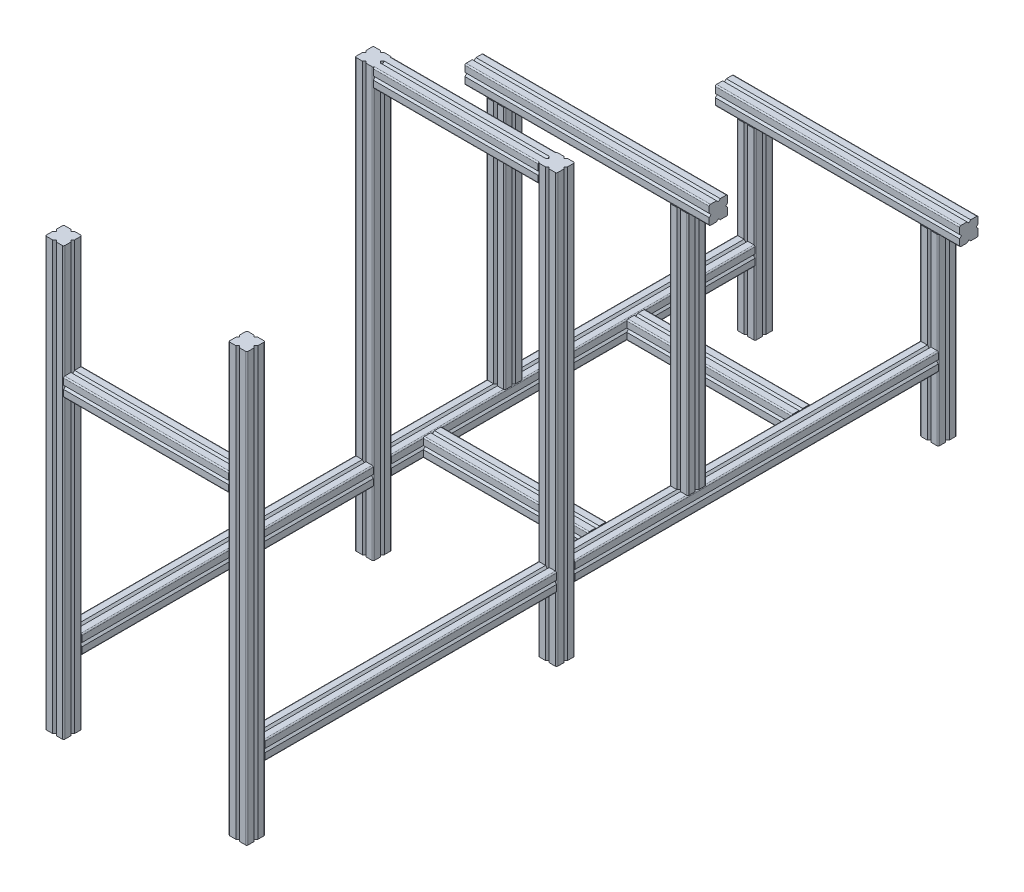
SolidWorks part; units mm, degrees
ref_plane "정면" through (0, 0, 0) normal (0, 0, 1) x (1, 0, 0)
ref_plane "윗면" through (0, 0, 0) normal (0, 1, 0) x (1, 0, 0)
ref_plane "우측면" through (0, 0, 0) normal (1, 0, 0) x (0, 0, -1)
sketch "스케치1" plane through (0, 0, 0) normal (0, 1, 0) x (1, 0, 0)
  line L0 (-150, 0) -> (150, 0) construction
  line L1 (135, 15) -> (165, 15) construction
  line L2 (135, 15) -> (135, -15) construction
  line L3 (135, -15) -> (165, -15) construction
  line L4 (165, 15) -> (165, -15) construction
  line L5 (135, 15) -> (165, -15) construction
  line L6 (135, -15) -> (165, 15) construction
  line L7 (-163, 15) -> (-153, 15)
  line L8 (-165, 13) -> (-165, 3)
  line L9 (-163, -15) -> (-153, -15)
  line L10 (-135, 13) -> (-135, 3)
  line L11 (-165, 15) -> (-135, -15) construction
  line L12 (-165, -15) -> (-135, 15) construction
  line L13 (-153, 15) -> (-150, 12)
  line L14 (-150, 12) -> (-147, 15)
  line L15 (-153, -15) -> (-150, -12)
  line L16 (-150, -12) -> (-147, -15)
  line L17 (-165, -3) -> (-162, 0)
  line L18 (-162, 0) -> (-165, 3)
  line L19 (-135, -3) -> (-138, 0)
  line L20 (-138, 0) -> (-135, 3)
  line L21 (-147, 15) -> (-137, 15)
  line L22 (-165, -3) -> (-165, -13)
  line L23 (-135, -3) -> (-135, -13)
  line L24 (-147, -15) -> (-137, -15)
  line L25 (0, 0) -> (0, 15) construction
  line L26 (165, -15) -> (135, 15) construction
  line L27 (165, 15) -> (135, -15) construction
  line L28 (147, -15) -> (137, -15)
  line L29 (135, -3) -> (135, -13)
  line L30 (165, -3) -> (165, -13)
  line L31 (147, 15) -> (137, 15)
  line L32 (138, 0) -> (135, 3)
  line L33 (135, -3) -> (138, 0)
  line L34 (162, 0) -> (165, 3)
  line L35 (165, -3) -> (162, 0)
  line L36 (150, -12) -> (147, -15)
  line L37 (153, -15) -> (150, -12)
  line L38 (150, 12) -> (147, 15)
  line L39 (153, 15) -> (150, 12)
  line L40 (135, 13) -> (135, 3)
  line L41 (163, -15) -> (153, -15)
  line L42 (165, 13) -> (165, 3)
  line L43 (163, 15) -> (153, 15)
  arc A0 (163, 15) -> (165, 13) centre (163, 13) cw
  arc A1 (163, -15) -> (165, -13) centre (163, -13) ccw
  arc A2 (135, -13) -> (137, -15) centre (137, -13) ccw
  arc A3 (135, 13) -> (137, 15) centre (137, 13) cw
  arc A4 (-137, -15) -> (-135, -13) centre (-137, -13) ccw
  arc A5 (-165, -13) -> (-163, -15) centre (-163, -13) ccw
  arc A6 (-163, 15) -> (-165, 13) centre (-163, 13) ccw
  arc A7 (-137, 15) -> (-135, 13) centre (-137, 13) cw
  point P0 (150, 0)
  point P5 (-150, 0)
  point P12 (0, 0)
  dimension "D2" = 2
  dimension "D1" = 300
  dimension "D4" = 30
  dimension "D6" = 6
extrude "보스-돌출1" add sketch "스케치1" along normal blind 700
sketch "스케치2" plane through (0, 0, 0) normal (0, 1, 0) x (1, 0, 0)
  line L0 (0, 0) -> (0, 625) construction
  line L1 (0, 625) -> (150, 625) construction
  line L2 (147, 640) -> (150, 637)
  line L3 (137, 610) -> (147, 610)
  line L4 (135, 612) -> (135, 622)
  line L5 (137, 640) -> (147, 640)
  line L6 (165, 612) -> (165, 622)
  line L7 (135, 610) -> (165, 640) construction
  line L8 (135, 640) -> (165, 610) construction
  line L9 (150, 637) -> (153, 640)
  line L10 (162, 625) -> (165, 628)
  line L11 (165, 622) -> (162, 625)
  line L12 (153, 610) -> (150, 613)
  line L13 (150, 613) -> (147, 610)
  line L14 (138, 625) -> (135, 622)
  line L15 (135, 628) -> (138, 625)
  line L16 (153, 640) -> (163, 640)
  line L17 (165, 628) -> (165, 638)
  line L18 (153, 610) -> (163, 610)
  line L19 (135, 628) -> (135, 638)
  line L20 (-135, 640) -> (-165, 610) construction
  line L21 (-135, 610) -> (-165, 640) construction
  line L22 (-135, 628) -> (-135, 638)
  line L23 (-153, 610) -> (-163, 610)
  line L24 (-165, 628) -> (-165, 638)
  line L25 (-153, 640) -> (-163, 640)
  line L26 (-135, 628) -> (-138, 625)
  line L27 (-138, 625) -> (-135, 622)
  line L28 (-150, 613) -> (-147, 610)
  line L29 (-153, 610) -> (-150, 613)
  line L30 (-165, 622) -> (-162, 625)
  line L31 (-162, 625) -> (-165, 628)
  line L32 (-150, 637) -> (-153, 640)
  line L33 (-165, 612) -> (-165, 622)
  line L50 (-137, 640) -> (-147, 640)
  line L51 (-135, 612) -> (-135, 622)
  line L52 (-137, 610) -> (-147, 610)
  line L53 (-147, 640) -> (-150, 637)
  arc A0 (-165, 612) -> (-163, 610) centre (-163, 612) ccw
  arc A1 (-137, 610) -> (-135, 612) centre (-137, 612) ccw
  arc A2 (-137, 640) -> (-135, 638) centre (-137, 638) cw
  arc A3 (-163, 640) -> (-165, 638) centre (-163, 638) ccw
  arc A4 (163, 610) -> (165, 612) centre (163, 612) ccw
  arc A5 (137, 610) -> (135, 612) centre (137, 612) cw
  arc A6 (163, 640) -> (165, 638) centre (163, 638) cw
  arc A7 (135, 638) -> (137, 640) centre (137, 638) cw
  point P15 (163.5, 623.5)
  point P16 (151.5, 611.5)
  point P39 (-151.5, 611.5)
  dimension "D4" = 2
  dimension "D1" = 625
  dimension "D2" = 150
  dimension "D3" = 30
  dimension "D5" = 6
extrude "보스-돌출2" add sketch "스케치2" along normal blind 300 separate body
sketch "스케치3" plane through (0, 0, 0) normal (0, 1, 0) x (1, 0, 0)
  line L0 (0, 0) -> (0, -507) construction
  line L1 (0, -507) -> (150, -507) construction
  line L2 (147, -492) -> (150, -495)
  line L3 (137, -522) -> (147, -522)
  line L4 (135, -520) -> (135, -510)
  line L5 (137, -492) -> (147, -492)
  line L6 (165, -520) -> (165, -510)
  line L7 (135, -522) -> (165, -492) construction
  line L8 (135, -492) -> (165, -522) construction
  line L9 (150, -495) -> (153, -492)
  line L10 (165, -510) -> (162, -507)
  line L11 (162, -507) -> (165, -504)
  line L12 (153, -522) -> (150, -519)
  line L13 (150, -519) -> (147, -522)
  line L14 (135, -504) -> (138, -507)
  line L15 (138, -507) -> (135, -510)
  line L16 (153, -492) -> (163, -492)
  line L17 (165, -504) -> (165, -494)
  line L18 (153, -522) -> (163, -522)
  line L19 (135, -504) -> (135, -494)
  line L20 (-135, -492) -> (-165, -522) construction
  line L21 (-135, -522) -> (-165, -492) construction
  line L22 (-135, -504) -> (-135, -494)
  line L23 (-153, -522) -> (-163, -522)
  line L24 (-165, -504) -> (-165, -494)
  line L25 (-153, -492) -> (-163, -492)
  line L26 (-138, -507) -> (-135, -510)
  line L27 (-135, -504) -> (-138, -507)
  line L28 (-150, -519) -> (-147, -522)
  line L29 (-153, -522) -> (-150, -519)
  line L30 (-162, -507) -> (-165, -504)
  line L31 (-165, -510) -> (-162, -507)
  line L32 (-150, -495) -> (-153, -492)
  line L33 (-165, -520) -> (-165, -510)
  line L34 (-137, -492) -> (-147, -492)
  line L35 (-135, -520) -> (-135, -510)
  line L36 (-137, -522) -> (-147, -522)
  line L37 (-147, -492) -> (-150, -495)
  arc A0 (-137, -522) -> (-135, -520) centre (-137, -520) ccw
  arc A1 (-165, -520) -> (-163, -522) centre (-163, -520) ccw
  arc A2 (-163, -492) -> (-165, -494) centre (-163, -494) ccw
  arc A3 (-137, -492) -> (-135, -494) centre (-137, -494) cw
  arc A4 (163, -522) -> (165, -520) centre (163, -520) ccw
  arc A5 (137, -522) -> (135, -520) centre (137, -520) cw
  arc A6 (135, -494) -> (137, -492) centre (137, -494) cw
  arc A7 (163, -492) -> (165, -494) centre (163, -494) cw
  dimension "D4" = 2
  dimension "D1" = 507
  dimension "D2" = 150
  dimension "D3" = 30
  dimension "D5" = 6
extrude "보스-돌출3" add sketch "스케치3" along normal blind 700 separate body
sketch "스케치5" plane through (0, 0, -15) normal (0, 0, -1) x (-1, 0, 0)
  line L0 (0, 0) -> (0, 120) construction
  line L1 (0, 120) -> (-150, 120) construction
  line L2 (-150, 300) -> (-150, 0) construction
  line L3 (-135, 300) -> (-135, 0) construction
  line L4 (-163, 135) -> (-153, 135)
  line L5 (-165, 133) -> (-165, 123)
  line L6 (-163, 105) -> (-153, 105)
  line L7 (-135, 133) -> (-135, 123)
  line L8 (-165, 135) -> (-135, 105) construction
  line L9 (-165, 105) -> (-135, 135) construction
  line L10 (-153, 135) -> (-150, 132)
  line L11 (-150, 132) -> (-147, 135)
  line L12 (-135, 117) -> (-138, 120)
  line L13 (-138, 120) -> (-135, 123)
  line L14 (-147, 105) -> (-150, 108)
  line L15 (-150, 108) -> (-153, 105)
  line L16 (-162, 120) -> (-165, 117)
  line L17 (-165, 123) -> (-162, 120)
  line L18 (-147, 135) -> (-137, 135)
  line L19 (-135, 117) -> (-135, 107)
  line L20 (-147, 105) -> (-137, 105)
  line L21 (-165, 117) -> (-165, 107)
  line L22 (165, 105) -> (135, 135) construction
  line L23 (165, 135) -> (135, 105) construction
  line L24 (165, 117) -> (165, 107)
  line L25 (147, 105) -> (137, 105)
  line L26 (135, 117) -> (135, 107)
  line L27 (147, 135) -> (137, 135)
  line L28 (165, 123) -> (162, 120)
  line L29 (162, 120) -> (165, 117)
  line L30 (150, 108) -> (153, 105)
  line L31 (147, 105) -> (150, 108)
  line L32 (138, 120) -> (135, 123)
  line L33 (135, 117) -> (138, 120)
  line L34 (150, 132) -> (147, 135)
  line L35 (153, 135) -> (150, 132)
  line L36 (135, 133) -> (135, 123)
  line L37 (163, 105) -> (153, 105)
  line L38 (165, 133) -> (165, 123)
  line L39 (163, 135) -> (153, 135)
  arc A0 (163, 135) -> (165, 133) centre (163, 133) cw
  arc A1 (163, 105) -> (165, 107) centre (163, 107) ccw
  arc A2 (135, 107) -> (137, 105) centre (137, 107) ccw
  arc A3 (135, 133) -> (137, 135) centre (137, 133) cw
  arc A4 (-137, 105) -> (-135, 107) centre (-137, 107) ccw
  arc A5 (-165, 107) -> (-163, 105) centre (-163, 107) ccw
  arc A6 (-137, 135) -> (-135, 133) centre (-137, 133) cw
  arc A7 (-163, 135) -> (-165, 133) centre (-163, 133) ccw
  dimension "D2" = 2
  dimension "D1" = 120
  dimension "D3" = 6
extrude "보스-돌출5" add sketch "스케치5" along normal blind 595
sketch "스케치6" plane through (0, 0, 492) normal (0, 0, -1) x (-1, 0, 0)
  line L0 (0, 0) -> (0, 120) construction
  line L1 (0, 120) -> (-150, 120) construction
  line L2 (-150, 300) -> (-150, 0) construction
  line L3 (-135, 300) -> (-135, 0) construction
  line L4 (-163, 105) -> (-153, 105)
  line L5 (-165, 107) -> (-165, 117)
  line L6 (-163, 135) -> (-153, 135)
  line L7 (-135, 107) -> (-135, 117)
  line L8 (-165, 105) -> (-135, 135) construction
  line L9 (-165, 135) -> (-135, 105) construction
  line L10 (-153, 135) -> (-150, 132)
  line L11 (-150, 132) -> (-147, 135)
  line L12 (-138, 120) -> (-135, 123)
  line L13 (-135, 117) -> (-138, 120)
  line L14 (-147, 105) -> (-150, 108)
  line L15 (-150, 108) -> (-153, 105)
  line L16 (-162, 120) -> (-165, 117)
  line L17 (-165, 123) -> (-162, 120)
  line L18 (-147, 135) -> (-137, 135)
  line L19 (-165, 123) -> (-165, 133)
  line L20 (-147, 105) -> (-137, 105)
  line L21 (-135, 123) -> (-135, 133)
  line L22 (165, 135) -> (135, 105) construction
  line L23 (165, 105) -> (135, 135) construction
  line L24 (135, 123) -> (135, 133)
  line L25 (147, 105) -> (137, 105)
  line L26 (165, 123) -> (165, 133)
  line L27 (147, 135) -> (137, 135)
  line L28 (165, 123) -> (162, 120)
  line L29 (162, 120) -> (165, 117)
  line L30 (150, 108) -> (153, 105)
  line L31 (147, 105) -> (150, 108)
  line L32 (135, 117) -> (138, 120)
  line L33 (138, 120) -> (135, 123)
  line L34 (150, 132) -> (147, 135)
  line L35 (153, 135) -> (150, 132)
  line L36 (135, 107) -> (135, 117)
  line L37 (163, 135) -> (153, 135)
  line L38 (165, 107) -> (165, 117)
  line L39 (163, 105) -> (153, 105)
  arc A0 (-163, 105) -> (-165, 107) centre (-163, 107) cw
  arc A1 (-137, 105) -> (-135, 107) centre (-137, 107) ccw
  arc A2 (-137, 135) -> (-135, 133) centre (-137, 133) cw
  arc A3 (-165, 133) -> (-163, 135) centre (-163, 133) cw
  arc A4 (165, 133) -> (163, 135) centre (163, 133) ccw
  arc A5 (137, 135) -> (135, 133) centre (137, 133) ccw
  arc A6 (137, 105) -> (135, 107) centre (137, 107) cw
  arc A7 (163, 105) -> (165, 107) centre (163, 107) ccw
  dimension "D4" = 2
  dimension "D1" = 120
  dimension "D3" = 6
extrude "보스-돌출6" add sketch "스케치6" along normal up to surface (477 mm away) up to face at (-142, 350, 15)
sketch "스케치7" plane through (0, 135, 0) normal (0, 1, 0) x (1, 0, 0)
  line L0 (0, 0) -> (0, 215) construction
  line L1 (0, 215) -> (150, 215) construction
  line L2 (150, 610) -> (150, 15) construction
  line L3 (165, 610) -> (165, 15) construction
  line L4 (137, 230) -> (147, 230)
  line L5 (135, 228) -> (135, 218)
  line L6 (137, 200) -> (147, 200)
  line L7 (165, 228) -> (165, 218)
  line L8 (135, 230) -> (165, 200) construction
  line L9 (135, 200) -> (165, 230) construction
  line L10 (147, 230) -> (150, 227)
  line L11 (150, 227) -> (153, 230)
  line L12 (162, 215) -> (165, 218)
  line L13 (165, 212) -> (162, 215)
  line L14 (153, 200) -> (150, 203)
  line L15 (150, 203) -> (147, 200)
  line L16 (138, 215) -> (135, 212)
  line L17 (135, 218) -> (138, 215)
  line L18 (153, 230) -> (163, 230)
  line L19 (135, 212) -> (135, 202)
  line L20 (153, 200) -> (163, 200)
  line L21 (165, 212) -> (165, 202)
  line L22 (-135, 200) -> (-165, 230) construction
  line L23 (-135, 230) -> (-165, 200) construction
  line L24 (-165, 212) -> (-165, 202)
  line L25 (-153, 200) -> (-163, 200)
  line L26 (-135, 212) -> (-135, 202)
  line L27 (-153, 230) -> (-163, 230)
  line L28 (-135, 218) -> (-138, 215)
  line L29 (-138, 215) -> (-135, 212)
  line L30 (-150, 203) -> (-147, 200)
  line L31 (-153, 200) -> (-150, 203)
  line L32 (-165, 212) -> (-162, 215)
  line L33 (-162, 215) -> (-165, 218)
  line L34 (-150, 227) -> (-153, 230)
  line L35 (-147, 230) -> (-150, 227)
  line L36 (-165, 228) -> (-165, 218)
  line L37 (-137, 200) -> (-147, 200)
  line L38 (-135, 228) -> (-135, 218)
  line L39 (-137, 230) -> (-147, 230)
  arc A0 (163, 230) -> (165, 228) centre (163, 228) cw
  arc A1 (163, 200) -> (165, 202) centre (163, 202) ccw
  arc A2 (135, 202) -> (137, 200) centre (137, 202) ccw
  arc A3 (137, 230) -> (135, 228) centre (137, 228) ccw
  arc A4 (-137, 230) -> (-135, 228) centre (-137, 228) cw
  arc A5 (-135, 202) -> (-137, 200) centre (-137, 202) cw
  arc A6 (-163, 200) -> (-165, 202) centre (-163, 202) cw
  arc A7 (-163, 230) -> (-165, 228) centre (-163, 228) ccw
  dimension "D4" = 2
  dimension "D1" = 215
  dimension "D3" = 6
extrude "보스-돌출7" add sketch "스케치7" along normal blind 400
sketch "스케치8" plane through (0, 0, 0) normal (1, 0, 0) x (0, 0, -1)
  line L0 (0, 0) -> (0, 120) construction
  line L1 (0, 700) -> (0, 0) construction
  line L2 (0, 120) -> (415, 120) construction
  line L3 (610, 120) -> (15, 120) construction
  line L4 (0, 120) -> (82, 120) construction
  line L5 (-3, 700) -> (0, 697)
  line L6 (-13, 700) -> (-3, 700)
  line L7 (-15, 698) -> (-15, 688)
  line L8 (-13, 670) -> (-3, 670)
  line L9 (15, 698) -> (15, 688)
  line L10 (-15, 700) -> (15, 670) construction
  line L11 (-15, 670) -> (15, 700) construction
  line L12 (0, 697) -> (3, 700)
  line L13 (12, 685) -> (15, 688)
  line L14 (15, 682) -> (12, 685)
  line L15 (3, 670) -> (0, 673)
  line L16 (0, 673) -> (-3, 670)
  line L17 (-12, 685) -> (-15, 682)
  line L18 (-15, 688) -> (-12, 685)
  line L19 (3, 700) -> (13, 700)
  line L20 (-15, 682) -> (-15, 672)
  line L21 (3, 670) -> (13, 670)
  line L22 (15, 682) -> (15, 672)
  line L23 (79, 135) -> (82, 132)
  line L24 (69, 135) -> (79, 135)
  line L25 (67, 133) -> (67, 123)
  line L26 (69, 105) -> (79, 105)
  line L27 (97, 133) -> (97, 123)
  line L28 (67, 135) -> (97, 105) construction
  line L29 (67, 105) -> (97, 135) construction
  line L30 (82, 132) -> (85, 135)
  line L31 (94, 120) -> (97, 123)
  line L32 (97, 117) -> (94, 120)
  line L33 (85, 105) -> (82, 108)
  line L34 (82, 108) -> (79, 105)
  line L35 (70, 120) -> (67, 117)
  line L36 (67, 123) -> (70, 120)
  line L37 (85, 135) -> (95, 135)
  line L38 (67, 117) -> (67, 107)
  line L39 (85, 105) -> (95, 105)
  line L40 (97, 117) -> (97, 107)
  line L41 (412, 135) -> (415, 132)
  line L42 (402, 135) -> (412, 135)
  line L43 (400, 133) -> (400, 123)
  line L44 (402, 105) -> (412, 105)
  line L45 (430, 133) -> (430, 123)
  line L46 (400, 135) -> (430, 105) construction
  line L47 (400, 105) -> (430, 135) construction
  line L48 (415, 132) -> (418, 135)
  line L49 (427, 120) -> (430, 123)
  line L50 (430, 117) -> (427, 120)
  line L51 (418, 105) -> (415, 108)
  line L52 (415, 108) -> (412, 105)
  line L53 (403, 120) -> (400, 117)
  line L54 (400, 123) -> (403, 120)
  line L55 (418, 135) -> (428, 135)
  line L56 (400, 117) -> (400, 107)
  line L57 (418, 105) -> (428, 105)
  line L58 (430, 117) -> (430, 107)
  line L59 (0, 700) -> (0, 685) construction
  line L60 (-510, 515) -> (-507, 512)
  line L61 (-520, 515) -> (-510, 515)
  line L62 (-522, 513) -> (-522, 503)
  line L63 (-520, 485) -> (-510, 485)
  line L64 (-492, 513) -> (-492, 503)
  line L65 (-522, 515) -> (-492, 485) construction
  line L66 (-522, 485) -> (-492, 515) construction
  line L67 (-507, 512) -> (-504, 515)
  line L68 (-495, 500) -> (-492, 503)
  line L69 (-492, 497) -> (-495, 500)
  line L70 (-504, 485) -> (-507, 488)
  line L71 (-507, 488) -> (-510, 485)
  line L72 (-519, 500) -> (-522, 497)
  line L73 (-522, 503) -> (-519, 500)
  line L74 (-504, 515) -> (-494, 515)
  line L75 (-522, 497) -> (-522, 487)
  line L76 (-504, 485) -> (-494, 485)
  line L77 (-492, 497) -> (-492, 487)
  line L78 (-507, 700) -> (-507, 500) construction
  arc A0 (13, 700) -> (15, 698) centre (13, 698) cw
  arc A1 (13, 670) -> (15, 672) centre (13, 672) ccw
  arc A2 (-15, 672) -> (-13, 670) centre (-13, 672) ccw
  arc A3 (-13, 700) -> (-15, 698) centre (-13, 698) ccw
  arc A4 (95, 135) -> (97, 133) centre (95, 133) cw
  arc A5 (95, 105) -> (97, 107) centre (95, 107) ccw
  arc A6 (67, 107) -> (69, 105) centre (69, 107) ccw
  arc A7 (69, 135) -> (67, 133) centre (69, 133) ccw
  arc A8 (428, 135) -> (430, 133) centre (428, 133) cw
  arc A9 (428, 105) -> (430, 107) centre (428, 107) ccw
  arc A10 (400, 107) -> (402, 105) centre (402, 107) ccw
  arc A11 (402, 135) -> (400, 133) centre (402, 133) ccw
  arc A12 (-494, 515) -> (-492, 513) centre (-494, 513) cw
  arc A13 (-494, 485) -> (-492, 487) centre (-494, 487) ccw
  arc A14 (-522, 487) -> (-520, 485) centre (-520, 487) ccw
  arc A15 (-520, 515) -> (-522, 513) centre (-520, 513) ccw
  point P10 (0, 685)
  point P41 (82, 120)
  point P70 (415, 120)
  point P102 (-507, 500)
  dimension "D7" = 2
  dimension "D4" = 2
  dimension "D1" = 120
  dimension "D2" = 415
  dimension "D3" = 333
  dimension "D5" = 30
  dimension "D6" = 6
  dimension "D8" = 30
  dimension "D9" = 6
  dimension "D10" = 6
  dimension "D11" = 30
  dimension "D12" = 15
  dimension "D13" = 6
  dimension "D14" = 30
  dimension "D15" = 200
extrude "보스-돌출8" add sketch "스케치8" along normal mid plane 270
sketch "스케치9" plane through (0, 0, 0) normal (1, 0, 0) x (0, 0, -1)
  line L0 (212, 565) -> (215, 562)
  line L1 (202, 565) -> (212, 565)
  line L2 (200, 563) -> (200, 553)
  line L3 (202, 535) -> (212, 535)
  line L4 (230, 563) -> (230, 553)
  line L5 (200, 565) -> (230, 535) construction
  line L6 (200, 535) -> (230, 565) construction
  line L7 (215, 562) -> (218, 565)
  line L8 (227, 550) -> (230, 553)
  line L9 (230, 547) -> (227, 550)
  line L10 (218, 535) -> (215, 538)
  line L11 (215, 538) -> (212, 535)
  line L12 (203, 550) -> (200, 547)
  line L13 (200, 553) -> (203, 550)
  line L14 (218, 565) -> (228, 565)
  line L15 (200, 547) -> (200, 537)
  line L16 (218, 535) -> (228, 535)
  line L17 (230, 547) -> (230, 537)
  line L18 (622, 330) -> (625, 327)
  line L19 (612, 330) -> (622, 330)
  line L20 (610, 328) -> (610, 318)
  line L21 (612, 300) -> (622, 300)
  line L22 (640, 328) -> (640, 318)
  line L23 (610, 330) -> (640, 300) construction
  line L24 (610, 300) -> (640, 330) construction
  line L25 (625, 327) -> (628, 330)
  line L26 (637, 315) -> (640, 318)
  line L27 (640, 312) -> (637, 315)
  line L28 (628, 300) -> (625, 303)
  line L29 (625, 303) -> (622, 300)
  line L30 (613, 315) -> (610, 312)
  line L31 (610, 318) -> (613, 315)
  line L32 (628, 330) -> (638, 330)
  line L33 (610, 312) -> (610, 302)
  line L34 (628, 300) -> (638, 300)
  line L35 (640, 312) -> (640, 302)
  arc A0 (228, 565) -> (230, 563) centre (228, 563) cw
  arc A1 (228, 535) -> (230, 537) centre (228, 537) ccw
  arc A2 (200, 537) -> (202, 535) centre (202, 537) ccw
  arc A3 (202, 565) -> (200, 563) centre (202, 563) ccw
  arc A4 (638, 330) -> (640, 328) centre (638, 328) cw
  arc A5 (638, 300) -> (640, 302) centre (638, 302) ccw
  arc A6 (610, 302) -> (612, 300) centre (612, 302) ccw
  arc A7 (612, 330) -> (610, 328) centre (612, 328) ccw
  point P0 (215, 550)
  point P32 (625, 315)
  dimension "D4" = 2
  dimension "D2" = 2
  dimension "D1" = 30
  dimension "D3" = 6
  dimension "D5" = 6
  dimension "D6" = 30
extrude "보스-돌출9" add sketch "스케치9" along normal mid plane 400
